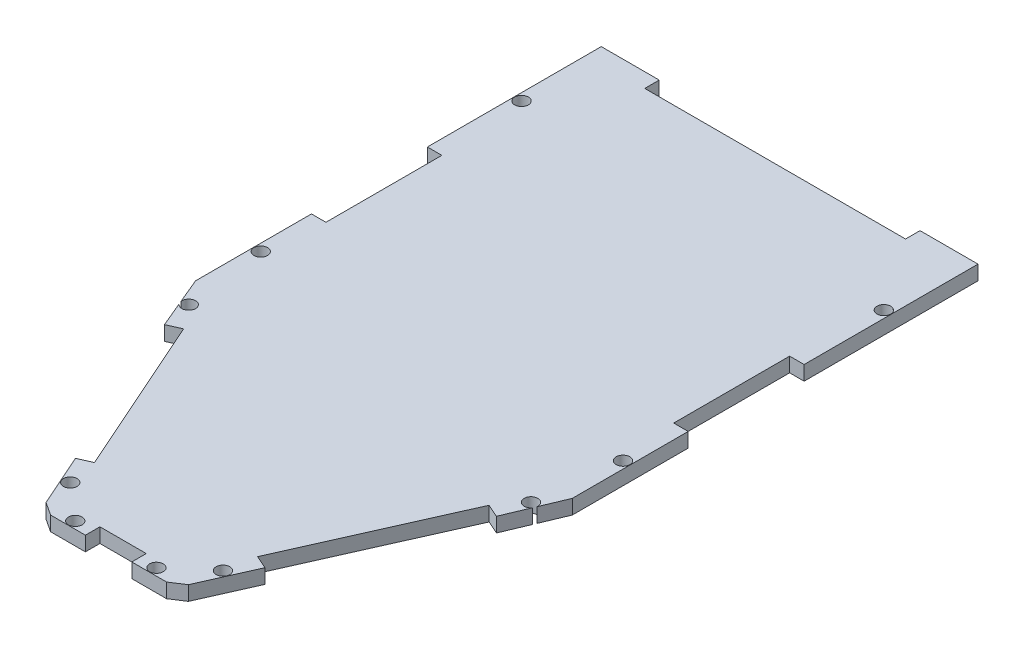
SolidWorks part; units mm, degrees
ref_plane "Front Plane" through (0, 0, 0) normal (0, 0, 1) x (1, 0, 0)
ref_plane "Top Plane" through (0, 0, 0) normal (0, 1, 0) x (1, 0, 0)
ref_plane "Right Plane" through (0, 0, 0) normal (1, 0, 0) x (0, 0, -1)
sketch "Sketch1" plane through (0, 0, 0) normal (0, 1, 0) x (1, 0, 0)
  line L0 (-41.275, 0) -> (-36.3683, -11.7139)
  line L1 (3.175, 88.9) -> (3.175, 85.725) construction
  line L2 (28.575, 85.725) -> (3.175, 85.725)
  line L3 (-41.275, 88.9) -> (-28.575, 88.9)
  line L4 (28.575, 88.9) -> (28.575, 85.725)
  line L5 (41.275, 50.8) -> (41.275, 88.9)
  line L6 (-41.275, 0) -> (-38.1, 0) construction
  line L7 (-41.275, 50.8) -> (-38.1, 50.8)
  line L8 (0, 63.5) -> (0, -63.5) construction
  line L9 (38.1, 50.8) -> (38.1, 25.4)
  line L10 (-38.1, 50.8) -> (-38.1, 25.4)
  line L11 (-41.275, 50.8) -> (-41.275, 88.9)
  line L12 (41.275, 50.8) -> (38.1, 50.8)
  line L13 (-28.575, 88.9) -> (-28.575, 85.725)
  line L14 (-28.575, 85.725) -> (-3.175, 85.725)
  line L15 (-3.175, 88.9) -> (-3.175, 85.725) construction
  line L16 (41.275, 88.9) -> (28.575, 88.9)
  line L17 (-41.275, 0) -> (41.275, 0) construction
  line L18 (-38.1, 0) -> (-38.1, 25.4) construction
  line L19 (-38.1, 25.4) -> (-41.275, 25.4)
  line L20 (-3.175, 88.9) -> (3.175, 88.9) construction
  line L21 (-41.275, 0) -> (-41.275, 25.4)
  line L22 (38.1, 25.4) -> (41.275, 25.4)
  line L23 (-38.1, 0) -> (-33.467, -10.4244) construction
  line L24 (41.275, 0) -> (41.275, 25.4)
  line L25 (33.467, -10.4244) -> (38.1, 0) construction
  line L26 (-36.3683, -11.7139) -> (-33.467, -10.4244) construction
  line L27 (41.275, 0) -> (36.3683, -11.7139)
  line L28 (36.3683, -11.7139) -> (33.467, -10.4244) construction
  line L29 (-17.858, -45.5446) -> (-12.7, -57.15) construction
  line L30 (-12.7, -57.15) -> (-15.6014, -58.4395) construction
  line L31 (-17.858, -45.5446) -> (-20.7593, -46.8341)
  line L32 (-15.6014, -58.4395) -> (-20.7593, -46.8341)
  line L33 (12.7, -57.15) -> (17.858, -45.5446) construction
  line L34 (-33.467, -10.4244) -> (-17.858, -45.5446)
  line L35 (-12.7, -57.15) -> (12.7, -57.15) construction
  line L36 (17.858, -45.5446) -> (33.467, -10.4244)
  line L37 (-3.175, 85.725) -> (3.175, 85.725)
  line L38 (41.275, 69.85) -> (-41.275, 69.85) construction
  line L39 (12.7, -57.15) -> (15.6014, -58.4395) construction
  line L40 (17.858, -45.5446) -> (20.7593, -46.8341)
  line L41 (15.6014, -58.4395) -> (20.7593, -46.8341)
  line L42 (38.1, 0) -> (38.1, 25.4) construction
  line L43 (-15.6014, -58.4395) -> (-12.7, -60.325)
  line L44 (-5.08, -57.15) -> (-12.7, -57.15) construction
  line L45 (-5.08, -57.15) -> (-5.08, -60.325)
  line L46 (-5.08, -60.325) -> (-12.7, -60.325)
  line L47 (-12.7, -57.15) -> (-12.7, -60.325) construction
  line L48 (5.08, -57.15) -> (12.7, -57.15) construction
  line L49 (5.08, -57.15) -> (5.08, -60.325)
  line L50 (5.08, -60.325) -> (12.7, -60.325)
  line L51 (12.7, -57.15) -> (12.7, -60.325) construction
  line L52 (15.6014, -58.4395) -> (12.7, -60.325)
  line L53 (-5.08, -57.15) -> (5.08, -57.15)
  line L54 (33.467, -10.4244) -> (36.3683, -11.7139)
  line L55 (-33.467, -10.4244) -> (-36.3683, -11.7139)
  point P0 (0, 0)
  point P1 (0, -57.15)
  dimension "D1" = 25.4
  dimension "D2" = 57.15
  dimension "D3" = 3.175
  dimension "D4" = 82.55
  dimension "D5" = 3.175
  dimension "D6" = 12.7
  dimension "D7" = 25.4
  dimension "D8" = 38.1
  dimension "D9" = 50.8
  dimension "D10" = 25.4
  dimension "D11" = 12.7
  dimension "D12" = 12.7
  dimension "D13" = 10.16
extrude "Boss-Extrude1" add sketch "Sketch1" along normal blind 3.175
sketch "Sketch2" plane through (0, 0, 0) normal (0, -1, 0) x (-1, 0, 0)
  line L0 (39.6875, 50.8) -> (39.6875, 88.9) construction
  line L1 (41.275, 50.8) -> (38.1, 50.8) construction
  line L2 (28.575, 88.9) -> (41.275, 88.9) construction
  line L3 (0, 85.725) -> (0, -57.15) construction
  line L6 (-5.08, -58.7375) -> (-15.1428, -58.7375) construction
  line L7 (5.08, -57.15) -> (-5.08, -57.15) construction
  line L10 (28.575, 88.9) -> (41.275, 88.9) construction
  line L11 (39.6875, 25.4) -> (39.6875, -3.7899) construction
  line L12 (38.1, 25.4) -> (41.275, 25.4) construction
  line L14 (-28.575, 85.725) -> (28.575, 85.725) construction
  line L15 (41.275, 0) -> (36.3683, -11.7139) construction
  line L18 (34.9176, -11.0691) -> (41.275, 3.235) construction
  line L23 (36.3683, -11.7139) -> (33.467, -10.4244) construction
  line L24 (41.275, 25.4) -> (41.275, 0) construction
  line L25 (19.3086, -46.1893) -> (13.0261, -60.325) construction
  line L26 (17.858, -45.5446) -> (20.7593, -46.8341) construction
  line L27 (12.7, -60.325) -> (5.08, -60.325) construction
  line L28 (5.08, -58.7375) -> (15.1428, -58.7375) construction
  line L29 (5.08, -60.325) -> (5.08, -57.15) construction
  line L30 (15.6014, -58.4395) -> (12.7, -60.325) construction
  line L31 (-19.3086, -46.1893) -> (-13.0261, -60.325) construction
  line L32 (-34.9176, -11.0691) -> (-41.275, 3.235) construction
  line L33 (-39.6875, 25.4) -> (-39.6875, -3.7899) construction
  line L34 (-39.6875, 50.8) -> (-39.6875, 88.9) construction
  circle A0 centre (39.6875, 69.85) radius 1.5
  circle A1 centre (-8.89, -58.7375) radius 1.5
  circle A2 centre (39.6875, 12.7) radius 1.5
  circle A3 centre (37.4966, -5.2664) radius 1.5
  circle A4 centre (16.7297, -51.992) radius 1.5
  circle A5 centre (8.89, -58.7375) radius 1.5
  circle A6 centre (-16.7297, -51.992) radius 1.5
  circle A7 centre (-37.4966, -5.2664) radius 1.5
  circle A8 centre (-39.6875, 12.7) radius 1.5
  circle A9 centre (-39.6875, 69.85) radius 1.5
  dimension "D1" = 3
  dimension "D4" = 6.35
  dimension "D6" = 3.81
  dimension "D2" = 3
  dimension "D3" = 12.7
  dimension "D5" = 6.35
extrude "Cut-Extrude1" cut sketch "Sketch2" against normal through all
